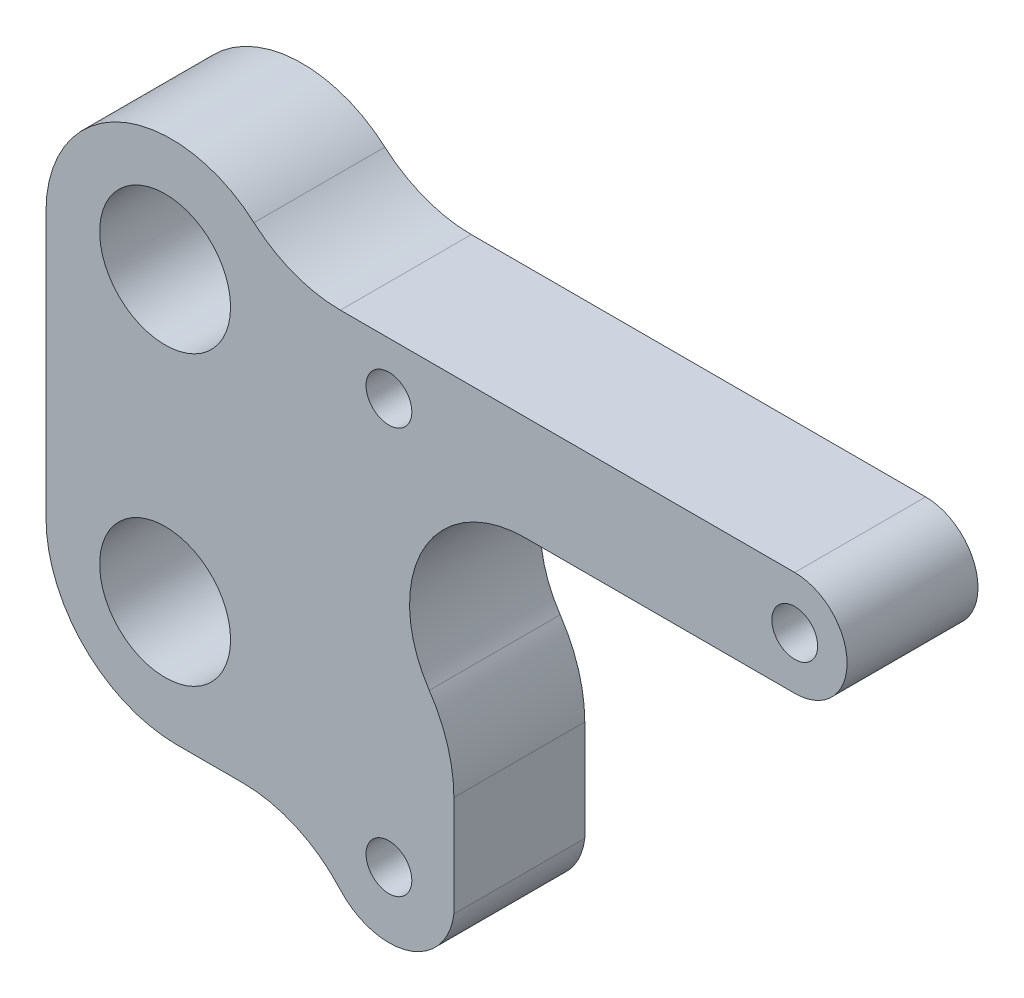
SolidWorks part; units mm, degrees
ref_plane "Piano frontale" through (0, 0, 0) normal (0, 0, 1) x (1, 0, 0)
ref_plane "Piano superiore" through (0, 0, 0) normal (0, 1, 0) x (1, 0, 0)
ref_plane "Piano destro" through (0, 0, 0) normal (1, 0, 0) x (0, 0, -1)
sketch "Sketch1" plane through (0, 0, 0) normal (0, 0, 1) x (1, 0, 0)
  line L0 (59.1153, 43.5513) -> (93.8228, 43.5513)
  line L1 (67.786, 7.9453) -> (67.786, 15.6436)
  line L2 (36.6269, 38.8486) -> (36.6269, 18.5513)
  line L3 (51.6425, 8.5513) -> (46.6269, 8.5513)
  line L4 (93.8228, 35.5513) -> (73.2211, 35.5513)
  line L6 (62.8228, -5.7466) -> (62.8228, 55.7339) construction
  line L7 (10.2847, 39.5513) -> (106.4029, 39.5513) construction
  arc A0 (59.096, 5.2179) -> (65.7153, 4.4728) centre (62.8228, 8.5513) ccw
  arc A1 (93.8228, 35.5513) -> (93.8228, 43.5513) centre (93.8228, 39.5513) ccw
  arc A2 (52.5151, 46.0388) -> (36.6269, 38.8486) centre (46.198, 38.8486) ccw
  arc A3 (46.6269, 8.5513) -> (36.6269, 18.5513) centre (46.6269, 18.5513) cw
  arc A4 (73.2211, 35.5513) -> (65.9057, 21.7942) centre (73.2211, 26.7278) ccw
  circle A5 centre (93.8228, 39.5513) radius 1.75
  circle A6 centre (62.8228, 39.5513) radius 1.75
  circle A7 centre (62.8228, 8.5513) radius 1.75
  arc A8 (67.786, 15.6436) -> (65.9057, 21.7942) centre (56.786, 15.6436) ccw
  arc A10 (65.7153, 4.4728) -> (67.786, 7.9453) centre (62.8228, 8.5513) ccw
  arc A11 (59.096, 5.2179) -> (51.6425, 8.5513) centre (51.6425, -1.4487) ccw
  arc A12 (59.1153, 43.5513) -> (52.5151, 46.0388) centre (59.1153, 53.5513) cw
  circle A13 centre (45.7251, 39.5513) radius 5
  circle A14 centre (45.7251, 17.5513) radius 5
  point P21 (45.7251, 39.5513)
  point P22 (45.7251, 17.5513)
  point P41 (57.8228, 8.5513)
  dimension "D2" = 31
  dimension "D4" = 10
  dimension "D5" = 11
  dimension "D6" = 10
  dimension "D7" = 8
  dimension "D9" = 5
  dimension "D10" = 10
  dimension "D11" = 10
  dimension "D12" = 10
  dimension "D13" = 3.5
  dimension "D1" = 22
  dimension "D3" = 31
extrude "Boss-Extrude1" add sketch "Sketch1" against normal blind 10
